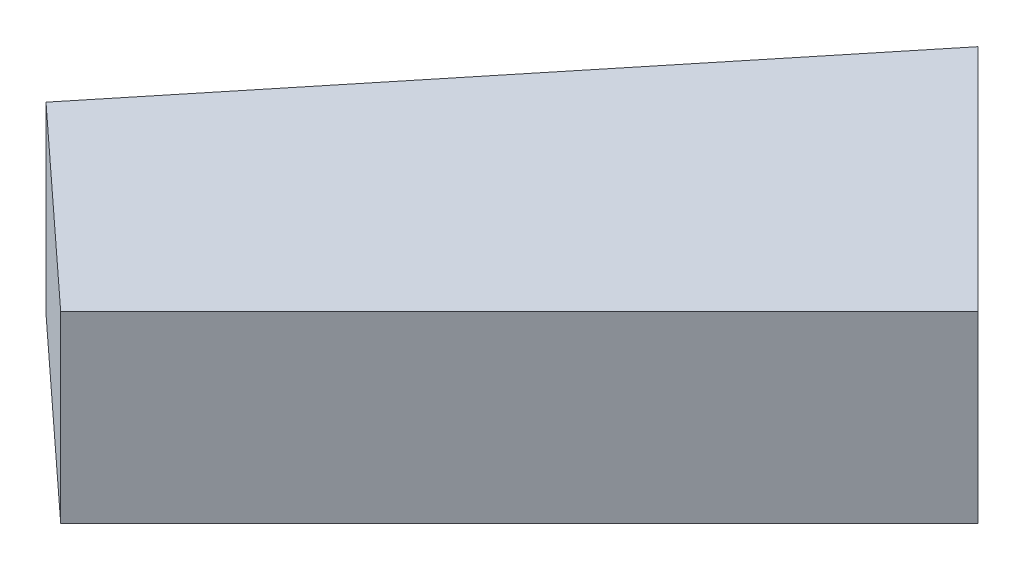
SolidWorks part; units mm, degrees
ref_plane "前视基准面" through (0, 0, 0) normal (0, 0, 1) x (1, 0, 0)
ref_plane "上视基准面" through (0, 0, 0) normal (0, 1, 0) x (1, 0, 0)
ref_plane "右视基准面" through (0, 0, 0) normal (1, 0, 0) x (0, 0, -1)
other "Configuration Table"
sketch "草图1" plane through (0, 0, 0) normal (0, 1, 0) x (1, 0, 0)
  line L0 (104.57, -48.37) -> (117.07, -35.87)
  line L1 (117.07, -35.87) -> (110.82, -29.62)
  line L2 (110.82, -29.62) -> (99.43, -43.63)
  line L3 (99.43, -43.63) -> (104.57, -48.37)
extrude "凸台-拉伸1" add sketch "草图1" along normal blind 5 from offset 9
